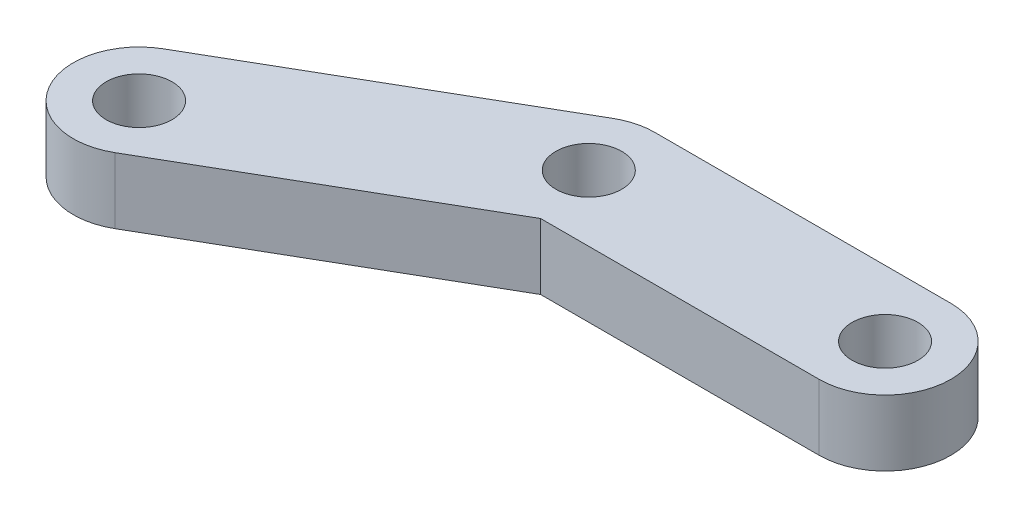
SolidWorks part; units mm, degrees
ref_plane "Front Plane" through (0, 0, 0) normal (0, 0, 1) x (1, 0, 0)
ref_plane "Top Plane" through (0, 0, 0) normal (0, 1, 0) x (1, 0, 0)
ref_plane "Right Plane" through (0, 0, 0) normal (1, 0, 0) x (0, 0, -1)
sketch "Sketch1" plane through (0, 0, 0) normal (0, 1, 0) x (1, 0, 0)
  line L0 (0, 0) -> (22.5, 0) construction
  line L1 (0, 5) -> (22.5, 5)
  line L2 (0, -5) -> (22.5, -5)
  arc A0 (0, 5) -> (0, -5) centre (0, 0) ccw
  arc A1 (22.5, -5) -> (22.5, 5) centre (22.5, 0) ccw
  circle A2 centre (0, 0) radius 2.5
  circle A3 centre (22.5, 0) radius 2.5
  point P3 (11.25, 0)
  dimension "D2" = 5
  dimension "D3" = 5
  dimension "D1" = 22.5
extrude "Boss-Extrude1" add sketch "Sketch1" along normal blind 5
sketch "Sketch2" plane through (0, 5, 0) normal (0, 1, 0) x (1, 0, 0)
  line L0 (0, 0) -> (-21.6506, -12.5) construction
  line L1 (2.5, -4.3301) -> (-19.1506, -16.8301)
  line L2 (-2.5, 4.3301) -> (-24.1506, -8.1699)
  line L3 (0, 0) -> (17.237, 0) construction
  arc A0 (2.5, -4.3301) -> (-2.5, 4.3301) centre (0, 0) ccw
  arc A1 (-24.1506, -8.1699) -> (-19.1506, -16.8301) centre (-21.6506, -12.5) ccw
  arc A2 (0, 5) -> (0, -5) centre (0, 0) ccw construction
  circle A3 centre (-21.6506, -12.5) radius 2.5
  circle A4 centre (0, 0) radius 2.5
  point P3 (-10.8253, -6.25)
  circle M2 centre (0, 0) radius 2.5
  arc M3 (0, 5) -> (0, -5) centre (0, 0) ccw
  line M4 (0, -5) -> (22.5, -5)
  dimension "D2" = 5
  dimension "D3" = 5
  dimension "D4" = 150
  dimension "D1" = 25
extrude "Boss-Extrude2" add sketch "Sketch2" against normal blind 5 contours L2 A1 L1 M4 M3 | L1 A0 M3 M4 M2
sketch "Sketch3" plane through (0, 5, 0) normal (0, 1, 0) x (1, 0, 0)
  circle A0 centre (22.5, 0) radius 3.75
  circle A1 centre (-21.6506, -12.5) radius 3.75
  dimension "D1" = 7.5
extrude "Cut-Extrude1" [suppressed] cut sketch "Sketch3" against normal blind 2.5
